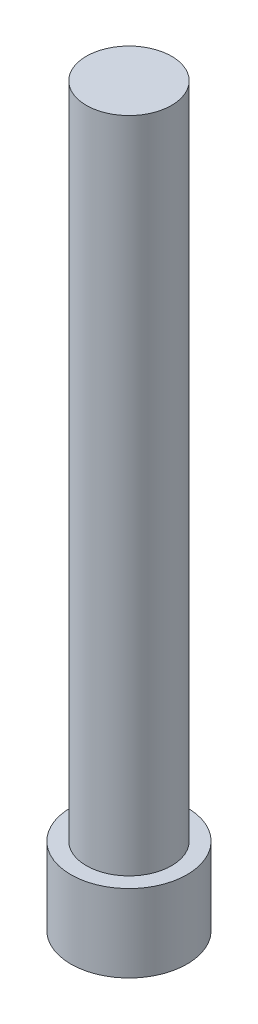
SolidWorks part; units mm, degrees
ref_plane "Front Plane" through (0, 0, 0) normal (0, 0, 1) x (1, 0, 0)
ref_plane "Top Plane" through (0, 0, 0) normal (0, 1, 0) x (1, 0, 0)
ref_plane "Right Plane" through (0, 0, 0) normal (1, 0, 0) x (0, 0, -1)
sketch "Sketch1" plane through (0, 0, 0) normal (0, 1, 0) x (1, 0, 0)
  circle A0 centre (0, 0) radius 7.5
  dimension "D1" = 15
extrude "Boss-Extrude2" add sketch "Sketch1" along normal blind 10
sketch "Sketch2" plane through (0, 10, 0) normal (0, 1, 0) x (1, 0, 0)
  circle A1 centre (0, 0) radius 5.5
  dimension "D1" = 11
extrude "Boss-Extrude4" add sketch "Sketch2" along normal blind 85
